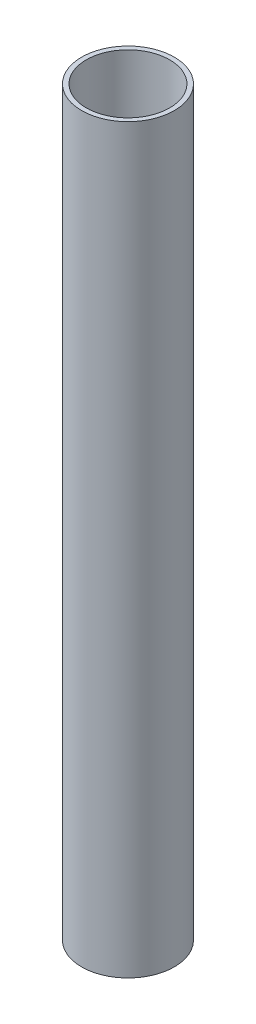
SolidWorks part; units mm, degrees
ref_plane "前视基准面" through (0, 0, 0) normal (0, 0, 1) x (1, 0, 0)
ref_plane "上视基准面" through (0, 0, 0) normal (0, 1, 0) x (1, 0, 0)
ref_plane "右视基准面" through (0, 0, 0) normal (1, 0, 0) x (0, 0, -1)
sketch "草图1" plane through (0, 0, 0) normal (0, 1, 0) x (1, 0, 0)
  circle A0 centre (0, 0) radius 10
  dimension "D1" = 20
extrude "1mm*30" add sketch "草图1" along normal mid plane 160 thin thin type one direction reverse wall 1
